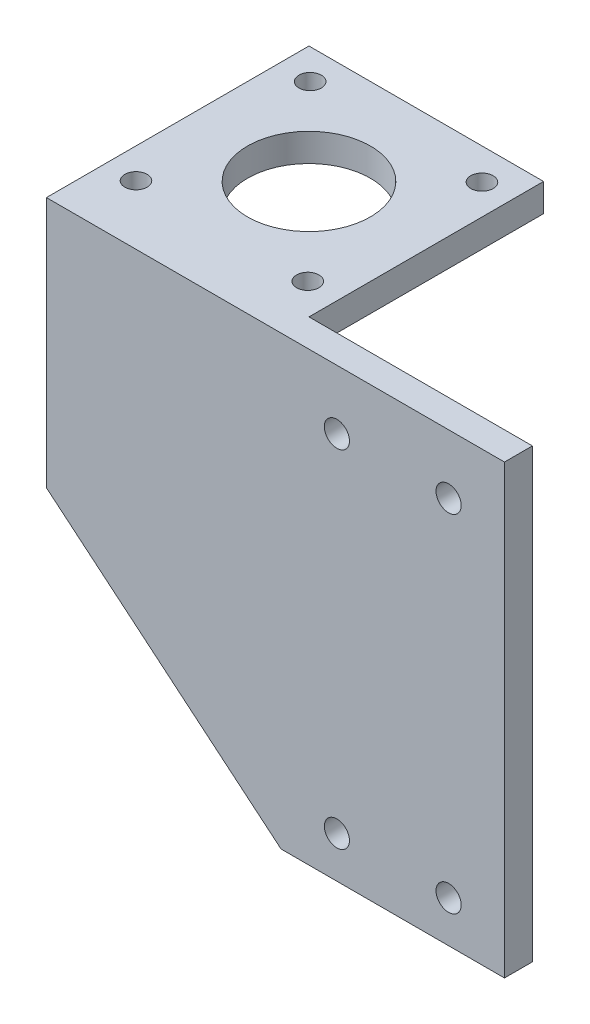
SolidWorks part; units mm, degrees
ref_plane "Front Plane" through (0, 0, 0) normal (0, 0, 1) x (1, 0, 0)
ref_plane "Top Plane" through (0, 0, 0) normal (0, 1, 0) x (1, 0, 0)
ref_plane "Right Plane" through (0, 0, 0) normal (1, 0, 0) x (0, 0, -1)
sketch "Sketch1" plane through (0, 0, 0) normal (0, 1, 0) x (1, 0, 0)
  line L0 (0, 0) -> (-19.9263, 20.2042) construction
  line L1 (0, 0) -> (17.8956, 17.6494) construction
  line L2 (0, 0) -> (17.1358, -17.3748) construction
  line L3 (0, 0) -> (-18.3532, -18.1007) construction
  line L5 (-21, -21) -> (21, -21)
  line L6 (-21, -21) -> (-21, 21)
  line L7 (-21, 21) -> (21, 21)
  line L8 (21, -21) -> (21, 21)
  line L9 (-21, -21) -> (21, 21) construction
  line L10 (-21, 21) -> (21, -21) construction
  circle A0 centre (0, 0) radius 11
  circle A1 centre (-15.5925, -15.378) radius 2
  circle A2 centre (-15.378, 15.5925) radius 2
  circle A3 centre (15.5925, 15.378) radius 2
  circle A4 centre (15.378, -15.5925) radius 2
  dimension "D1" = 22
  dimension "D2" = 4
  dimension "D4" = 21.9
  dimension "D3" = 21.9
  dimension "D5" = 21.9
  dimension "D6" = 21.9
  dimension "D7" = 42
extrude "Boss-Extrude1" add sketch "Sketch1" along normal blind 5
sketch "Sketch2" plane through (0, 0, 21) normal (0, 0, 1) x (1, 0, 0)
  line L0 (21, 5) -> (61, 5)
  line L1 (61, 5) -> (61, -75)
  line L2 (61, -75) -> (21, -75)
  line L3 (-21, 0) -> (-21, -40)
  line L4 (-21, 0) -> (-21, 5)
  line L5 (-21, 5) -> (21, 5)
  line L6 (-21, -40) -> (21, -75)
  line L7 (41, -75) -> (41, 5) construction
  line L8 (31, -5.6273) -> (41, -5.6273) construction
  line L9 (41, -5.6273) -> (51, -5.6273) construction
  line L10 (31, -67.5818) -> (41, -67.5818) construction
  line L11 (41, -67.5818) -> (51, -67.5818) construction
  circle A0 centre (51, -67.5818) radius 2.25
  circle A1 centre (31, -67.5818) radius 2.25
  circle A2 centre (31, -5.6273) radius 2.25
  circle A3 centre (51, -5.6273) radius 2.25
  dimension "D4" = 4.5
  dimension "D1" = 40
  dimension "D2" = 80
  dimension "D3" = 40
  dimension "D5" = 10
extrude "Boss-Extrude2" add sketch "Sketch2" along normal blind 5
